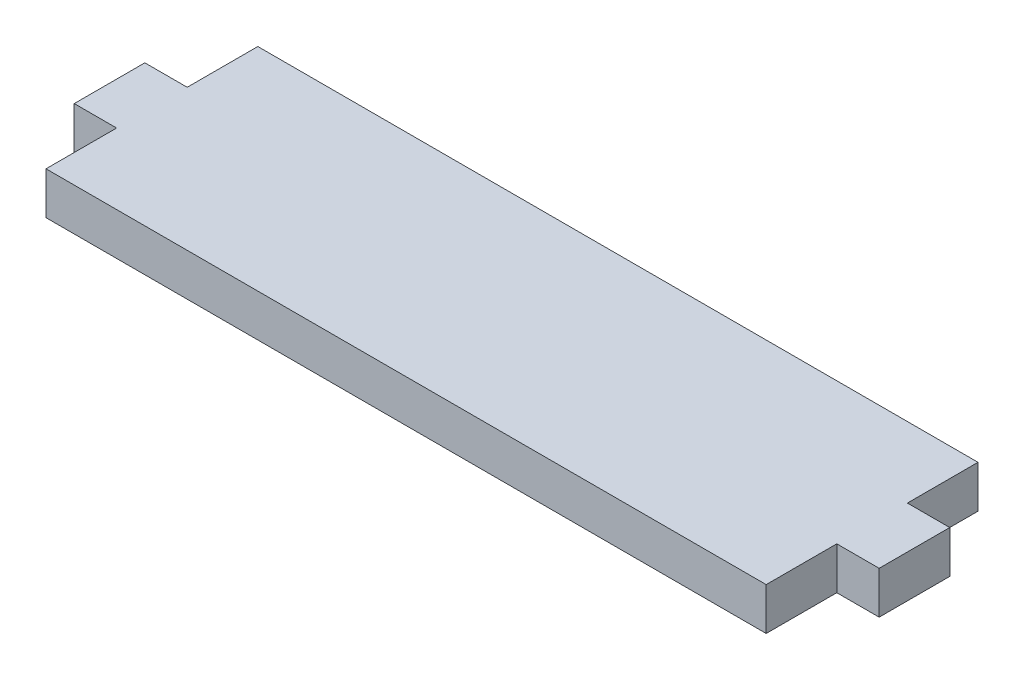
SolidWorks part; units mm, degrees
ref_plane "Front Plane" through (0, 0, 0) normal (0, 0, 1) x (1, 0, 0)
ref_plane "Top Plane" through (0, 0, 0) normal (0, 1, 0) x (1, 0, 0)
ref_plane "Right Plane" through (0, 0, 0) normal (1, 0, 0) x (0, 0, -1)
sketch "Sketch1" plane through (0, 0, 0) normal (0, 1, 0) x (1, 0, 0)
  line L1 (-54, -15) -> (48, -15)
  line L2 (-54, 15) -> (48, 15)
  line L5 (54, 5) -> (54, -5)
  line L6 (54, 5) -> (48, 5)
  line L7 (54, -5) -> (48, -5)
  line L10 (-60, -5) -> (-54, -5)
  line L11 (-60, 5) -> (-60, -5)
  line L12 (-60, 5) -> (-54, 5)
  line L14 (-54, -5) -> (-54, -15)
  line L15 (-54, 5) -> (-54, 15)
  line L16 (48, 5) -> (48, 15)
  line L17 (48, -5) -> (48, -15)
  point P4 (0, 0)
  point P11 (54, 0)
  dimension "D1" = 102
  dimension "D2" = 10
  dimension "D4" = 6
  dimension "D5" = 30
extrude "Boss-Extrude1" add sketch "Sketch1" along normal blind 6
